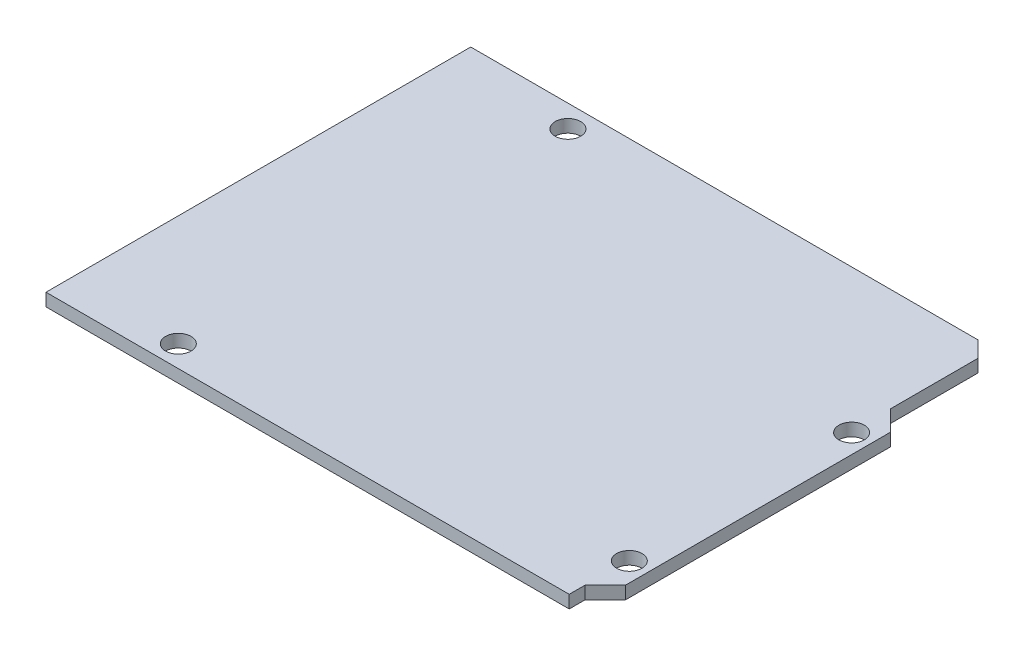
SolidWorks part; units mm, degrees
ref_plane "Front Plane" through (0, 0, 0) normal (0, 0, 1) x (1, 0, 0)
ref_plane "Top Plane" through (0, 0, 0) normal (0, 1, 0) x (1, 0, 0)
ref_plane "Right Plane" through (0, 0, 0) normal (1, 0, 0) x (0, 0, -1)
sketch "Sketch3" plane through (0, 0, 0) normal (0, 1, 0) x (1, 0, 0)
  line L0 (-34.1, 26.65) -> (29.56, 26.65)
  line L1 (34.1, 26.65) -> (-34.1, 26.65) construction
  line L2 (34.1, 26.65) -> (34.1, -26.65) construction
  line L3 (34.1, -26.65) -> (-34.1, -26.65) construction
  line L4 (-34.1, 26.65) -> (-34.1, -26.65)
  line L5 (34.1, 26.65) -> (-34.1, -26.65) construction
  line L6 (34.1, -26.65) -> (-34.1, 26.65) construction
  line L7 (29.56, 26.65) -> (31.56, 24.65)
  line L8 (31.56, 24.65) -> (31.56, 13.7)
  line L9 (31.56, 13.7) -> (34.1, 11.16)
  line L10 (34.1, 11.16) -> (34.1, -22.11)
  line L11 (34.1, -22.11) -> (31.56, -24.65)
  line L12 (31.56, -24.65) -> (31.56, -26.65)
  line L13 (31.56, -26.65) -> (-34.1, -26.65)
  point P0 (0, 0)
  point P6 (0, 0)
  dimension "D1" = 68.2
  dimension "D2" = 53.3
  dimension "D3" = 2
  dimension "D4" = 2.54
  dimension "D5" = 2
  dimension "D6" = 2
  dimension "D7" = 2.54
  dimension "D8" = 12.95
extrude "Boss-Extrude1" add sketch "Sketch3" along normal blind 1.6
sketch "Sketch4" plane through (0, 1.6, 0) normal (0, 1, 0) x (1, 0, 0)
  line L0 (-34.1, -26.65) -> (31.56, -26.65) construction
  line L1 (-34.1, 26.65) -> (-34.1, -26.65) construction
  circle A0 centre (-19.1, 23.85) radius 1.6
  circle A2 centre (31.7, 8.65) radius 1.6
  circle A3 centre (31.7, -19.25) radius 1.6
  circle A4 centre (-20.2, -23.95) radius 1.6
  dimension "D1" = 3.2
  dimension "D2" = 50.8
  dimension "D3" = 51.9
  dimension "D4" = 27.9
  dimension "D5" = 15.2
  dimension "D6" = 4.7
  dimension "D7" = 50.5
  dimension "D8" = 15
extrude "Cut-Extrude1" cut sketch "Sketch4" against normal blind 1.6
